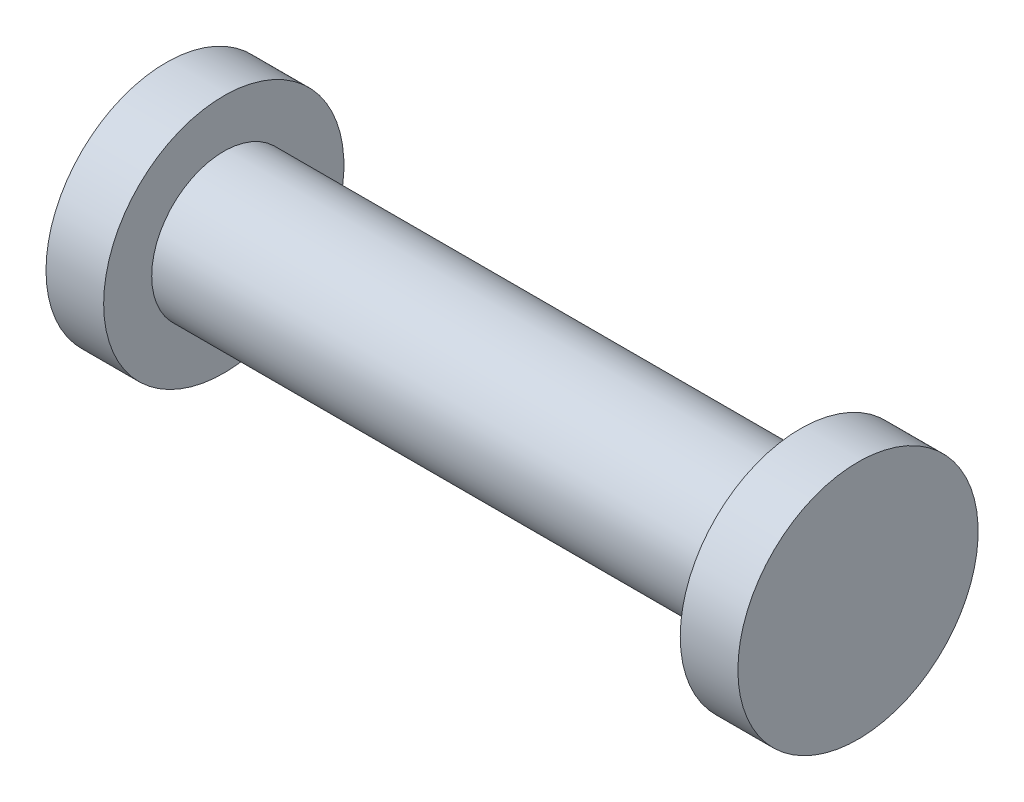
SolidWorks part; units mm, degrees
material "Plain Carbon Steel"
ref_plane "Front Plane" through (0, 0, 0) normal (0, 0, 1) x (1, 0, 0)
ref_plane "Top Plane" through (0, 0, 0) normal (0, 1, 0) x (1, 0, 0)
ref_plane "Right Plane" through (0, 0, 0) normal (1, 0, 0) x (0, 0, -1)
sketch "Sketch1" plane through (0, 0, 0) normal (0, 1, 0) x (1, 0, 0)
  line L0 (-414.0168, 0) -> (20286.825, 0) construction
  line L1 (0, 0) -> (-36, 0)
  line L2 (-36, 0) -> (-36, 12.5)
  line L3 (-36, 12.5) -> (-30, 12.5)
  line L4 (-30, 12.5) -> (-30, 7.5)
  line L5 (-30, 7.5) -> (30, 7.5)
  line L6 (30, 7.5) -> (30, 12.5)
  line L7 (30, 12.5) -> (36, 12.5)
  line L8 (36, 12.5) -> (36, 0)
  line L9 (36, 0) -> (0, 0)
  point P9 (0, 7.5)
  dimension "D1" = 60
  dimension "D2" = 7.5
  dimension "D3" = 12.5
  dimension "D4" = 6
revolve "Revolve1" add sketch "Sketch1" angle 360 about L0
